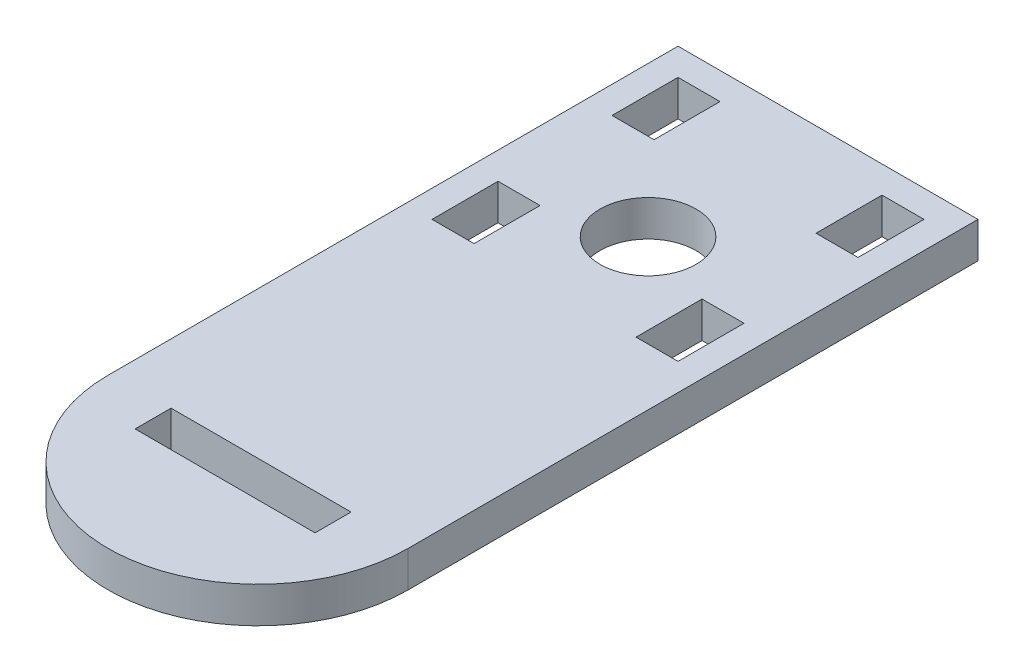
SolidWorks part; units mm, degrees
ref_plane "Front Plane" through (0, 0, 0) normal (0, 0, 1) x (1, 0, 0)
ref_plane "Top Plane" through (0, 0, 0) normal (0, 1, 0) x (1, 0, 0)
ref_plane "Right Plane" through (0, 0, 0) normal (1, 0, 0) x (0, 0, -1)
sketch "Sketch1" plane through (0, 0, 0) normal (0, 1, 0) x (1, 0, 0)
  line L0 (0, 0) -> (-25, 0)
  line L3 (-25, 0) -> (-25, -47.5)
  line L4 (0, 0) -> (0, -47.5)
  line L6 (-22.75, -2.25) -> (-19.25, -2.25)
  line L7 (-22.75, -2.25) -> (-22.75, -7.75)
  line L8 (-22.75, -7.75) -> (-19.25, -7.75)
  line L9 (-19.25, -2.25) -> (-19.25, -7.75)
  line L10 (-5.75, -2.25) -> (-2.25, -2.25)
  line L11 (-5.75, -2.25) -> (-5.75, -7.75)
  line L12 (-5.75, -7.75) -> (-2.25, -7.75)
  line L13 (-2.25, -2.25) -> (-2.25, -7.75)
  line L14 (-22.75, -17.25) -> (-19.25, -17.25)
  line L15 (-22.75, -17.25) -> (-22.75, -22.75)
  line L16 (-22.75, -22.75) -> (-19.25, -22.75)
  line L17 (-19.25, -17.25) -> (-19.25, -22.75)
  line L18 (-5.75, -17.25) -> (-2.25, -17.25)
  line L19 (-5.75, -17.25) -> (-5.75, -22.75)
  line L20 (-5.75, -22.75) -> (-2.25, -22.75)
  line L21 (-2.25, -17.25) -> (-2.25, -22.75)
  line L22 (-20, -47.25) -> (-5, -47.25)
  line L23 (-20, -47.25) -> (-20, -50.25)
  line L24 (-20, -50.25) -> (-5, -50.25)
  line L25 (-5, -47.25) -> (-5, -50.25)
  line L26 (-20, -47.25) -> (-5, -50.25) construction
  line L27 (-20, -50.25) -> (-5, -47.25) construction
  arc A2 (-25, -47.5) -> (0, -47.5) centre (-12.5, -47.5) ccw
  circle A3 centre (-12.5, -15) radius 4
  point P6 (-12.5, -60)
  point P24 (-12.5, -47.25)
  point P25 (-12.5, 0)
  point P27 (-12.5, -48.75)
  point P33 (-14.2833, -16.5)
  dimension "D13" = 8
  dimension "D1" = 25
  dimension "D2" = 60
  dimension "D3" = 3.5
  dimension "D4" = 5.5
  dimension "D5" = 20.5
  dimension "D6" = 20.5
  dimension "D7" = 2.25
  dimension "D8" = 2.25
  dimension "D9" = 45
  dimension "D10" = 3
  dimension "D11" = 15
  dimension "D12" = 12.75
extrude "Boss-Extrude1" add sketch "Sketch1" along normal blind 3
equation "\"D8@Sketch1\"=\"D7@Sketch1\""
